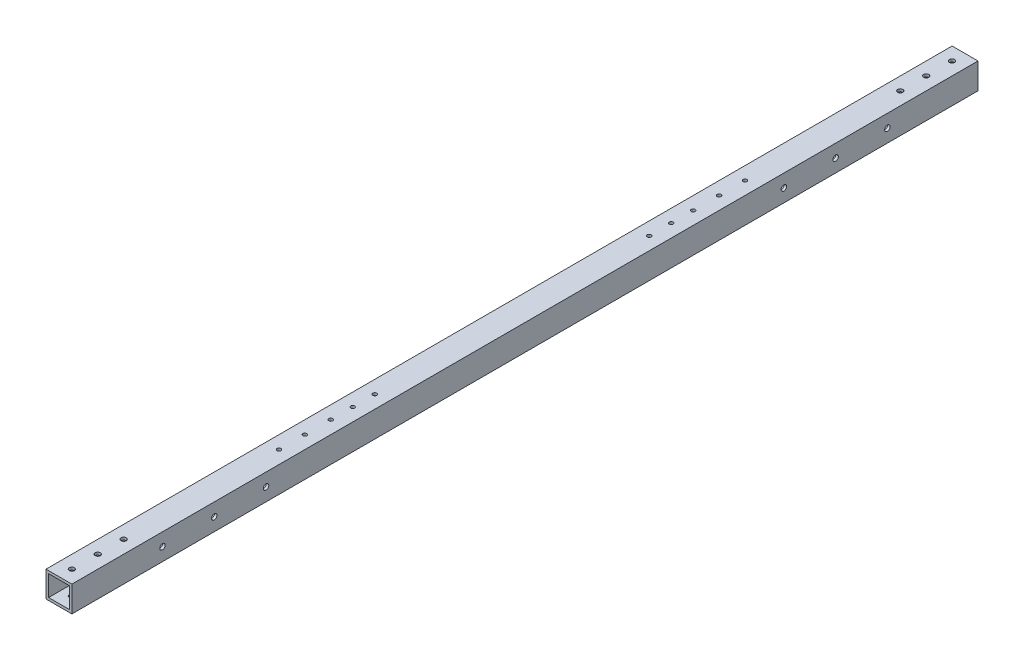
SolidWorks part; units mm, degrees
material "6061 合金"
ref_plane "前视基准面" through (0, 0, 0) normal (0, 0, 1) x (1, 0, 0)
ref_plane "上视基准面" through (0, 0, 0) normal (0, 1, 0) x (1, 0, 0)
ref_plane "右视基准面" through (0, 0, 0) normal (1, 0, 0) x (0, 0, -1)
other "Configuration Table"
sketch "草图1" plane through (0, 0, 0) normal (0, 0, 1) x (1, 0, 0)
  line L1 (0, 0) -> (20, 0)
  line L2 (0, 0) -> (0, 20)
  line L3 (0, 20) -> (20, 20)
  line L4 (20, 0) -> (20, 20)
  dimension "D1" = 20
  dimension "D2" = 20
extrude "拉伸-薄壁1" add sketch "草图1" along normal blind 700 thin thin type one direction reverse wall 2
sketch "草图2" plane through (0, 0, 0) normal (-1, 0, 0) x (0, 0, 1)
  line L0 (0, 10) -> (66.7299, 10) construction
  line L1 (0, 20) -> (0, 0) construction
  line L2 (350, 20) -> (350, 0) construction
  line L3 (700, 20) -> (0, 20) construction
  line L4 (700, 0) -> (0, 0) construction
  circle A0 centre (10, 10) radius 2
  circle A1 centre (30, 10) radius 2
  circle A2 centre (50, 10) radius 2
  circle A3 centre (690, 10) radius 2
  circle A4 centre (670, 10) radius 2
  circle A5 centre (650, 10) radius 2
  dimension "D1" = 4
  dimension "D2" = 10
  dimension "D3" = 20
  dimension "D4" = 20
extrude "切除-拉伸1" [suppressed] cut sketch "草图2" against normal through all
sketch "草图3" plane through (0, 0, 0) normal (0, -1, 0) x (1, 0, 0)
  line L0 (10, 0) -> (10, 51.2386) construction
  line L1 (0, 0) -> (20, 0) construction
  line L2 (0, 350) -> (20, 350) construction
  line L3 (0, 700) -> (0, 0) construction
  line L4 (20, 700) -> (20, 0) construction
  circle A0 centre (10, 10) radius 2
  circle A1 centre (10, 30) radius 2
  circle A2 centre (10, 50) radius 2
  circle A3 centre (10, 690) radius 2
  circle A4 centre (10, 670) radius 2
  circle A5 centre (10, 650) radius 2
  dimension "D1" = 4
  dimension "D2" = 10
  dimension "D3" = 20
  dimension "D4" = 20
extrude "切除-拉伸2" cut sketch "草图3" against normal through all
sketch "草图4" plane through (0, 0, 0) normal (0, -1, 0) x (1, 0, 0)
  line L0 (10, 700) -> (10, 0) construction
  line L1 (0, 700) -> (20, 700) construction
  line L2 (0, 0) -> (20, 0) construction
  line L3 (0, 350) -> (20, 350) construction
  line L4 (0, 700) -> (0, 0) construction
  line L5 (20, 700) -> (20, 0) construction
  circle A0 centre (10, 170) radius 1.5
  circle A1 centre (10, 190) radius 1.5
  circle A2 centre (10, 210) radius 1.5
  circle A3 centre (10, 490) radius 1.5
  circle A4 centre (10, 510) radius 1.5
  circle A5 centre (10, 530) radius 1.5
  circle A6 centre (10, 473) radius 1.5
  circle A7 centre (10, 456) radius 1.5
  circle A8 centre (10, 227) radius 1.5
  circle A9 centre (10, 244) radius 1.5
  dimension "D1" = 3
  dimension "D2" = 170
  dimension "D3" = 20
  dimension "D4" = 20
  dimension "D5" = 17
  dimension "D6" = 17
  dimension "D7" = 17
  dimension "D8" = 17
extrude "切除-拉伸3" cut sketch "草图4" against normal through all
sketch "草图5" plane through (20, 0, 0) normal (1, 0, 0) x (0, 0, -1)
  line L0 (0, 10) -> (-70, 10) construction
  line L1 (0, 0) -> (0, 20) construction
  line L2 (-350, 20) -> (-350, 0) construction
  line L3 (-700, 20) -> (0, 20) construction
  line L4 (-700, 0) -> (0, 0) construction
  circle A0 centre (-70, 10) radius 2.1
  circle A1 centre (-110, 10) radius 2.1
  circle A2 centre (-150, 10) radius 2.1
  circle A3 centre (-550, 10) radius 2.1
  circle A4 centre (-590, 10) radius 2.1
  circle A5 centre (-630, 10) radius 2.1
  dimension "D2" = 4.2
  dimension "D4" = 40
  dimension "D1" = 70
  dimension "D3" = 3
extrude "切除-拉伸4" cut sketch "草图5" against normal through all
